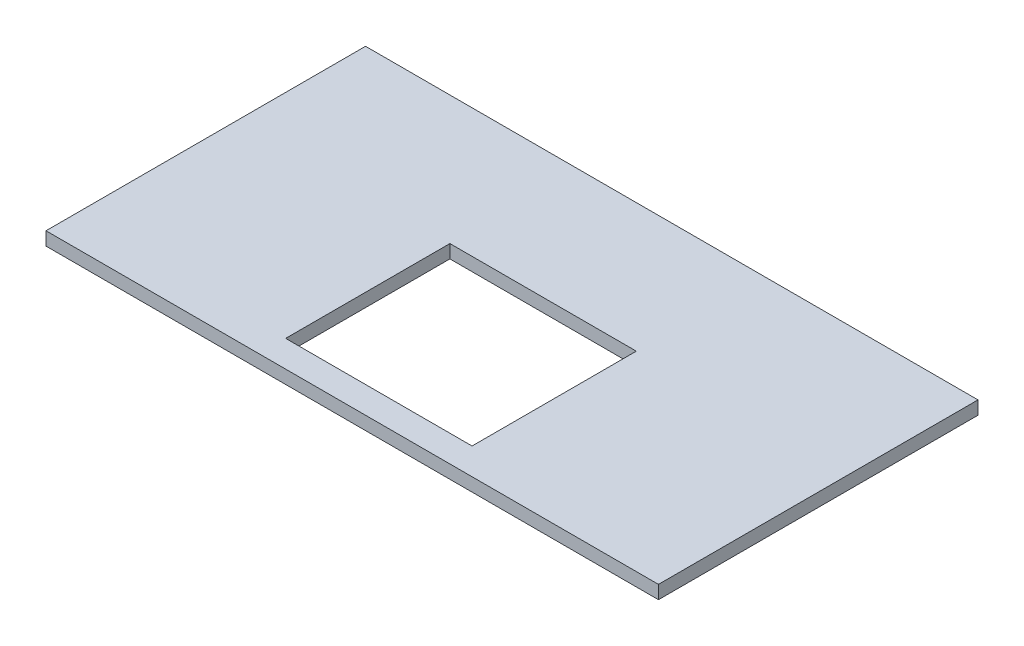
SolidWorks part; units mm, degrees
ref_plane "Front Plane" through (0, 0, 0) normal (0, 0, 1) x (1, 0, 0)
ref_plane "Top Plane" through (0, 0, 0) normal (0, 1, 0) x (1, 0, 0)
ref_plane "Right Plane" through (0, 0, 0) normal (1, 0, 0) x (0, 0, -1)
sketch "Sketch1" plane through (0, 0, 0) normal (0, 1, 0) x (1, 0, 0)
  line L1 (0, 0) -> (146.05, 0)
  line L2 (0, 0) -> (0, 76.2)
  line L3 (0, 76.2) -> (146.05, 76.2)
  line L4 (146.05, 0) -> (146.05, 76.2)
  line L5 (50.8, 6.35) -> (95.25, 6.35)
  line L6 (50.8, 6.35) -> (50.8, 45.5168)
  line L7 (50.8, 45.5168) -> (95.25, 45.5168)
  line L8 (95.25, 6.35) -> (95.25, 45.5168)
  dimension "D1" = 76.2
  dimension "D2" = 146.05
  dimension "D3" = 39.1668
  dimension "D4" = 44.45
  dimension "D5" = 50.8
  dimension "D6" = 6.35
extrude "Boss-Extrude1" add sketch "Sketch1" along normal blind 3.175
